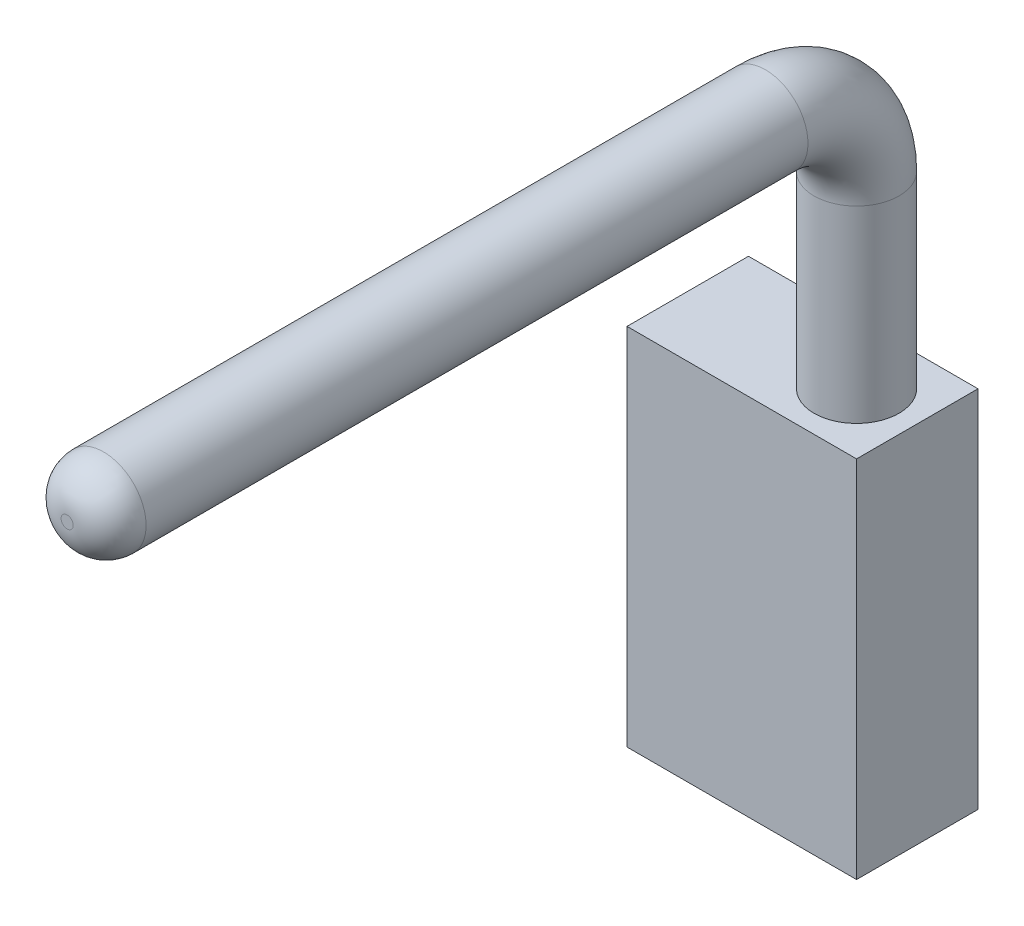
SolidWorks part; units mm, degrees
ref_plane "Front Plane" through (0, 0, 0) normal (1, 0, 0) x (0, 1, 0)
ref_plane "Top Plane" through (0, 0, 0) normal (0, 0, 1) x (0, 1, 0)
ref_plane "Right Plane" through (0, 0, 0) normal (0, 1, 0) x (-1, 0, 0)
sketch "Sketch1" plane through (0, 0, 0) normal (0, 0, 1) x (0, 1, 0)
  line L1 (-19.05, -12.0015) -> (19.05, -12.0015)
  line L2 (-19.05, -12.0015) -> (-19.05, 12.0015)
  line L3 (-19.05, 12.0015) -> (19.05, 12.0015)
  line L4 (19.05, -12.0015) -> (19.05, 12.0015)
  line L5 (-19.05, -12.0015) -> (19.05, 12.0015) construction
  line L6 (-19.05, 12.0015) -> (19.05, -12.0015) construction
  point P0 (0, 0)
  dimension "D1" = 38.1
  dimension "D2" = 24.003
extrude "Boss-Extrude1" add sketch "Sketch1" along normal blind 12.7
ref_plane "Plane1" through (5.6515, 0, 0) normal (1, 0, 0) x (0, 0, -1)
sketch "Sketch2" plane through (5.6515, 0, 0) normal (1, 0, 0) x (0, 0, -1)
  line L0 (-6.35, 19.05) -> (-6.35, 38.735)
  line L1 (-12.7, 19.05) -> (0, 19.05) construction
  line L2 (-15.875, 48.26) -> (-88.9, 48.26)
  arc A0 (-6.35, 38.735) -> (-15.875, 48.26) centre (-15.875, 38.735) ccw
  dimension "D1" = 9.525
  dimension "D2" = 82.55
  dimension "D3" = 29.21
sketch "Sketch3" plane through (0, 19.05, 0) normal (0, 1, 0) x (-1, 0, 0)
  line L0 (-5.6515, 15.875) -> (-5.6515, 6.35) construction
  line L1 (-5.6515, 6.985) -> (-5.6515, -6.985) construction
  circle A0 centre (-5.6515, 6.35) radius 4.445
  point P6 (-5.6515, 6.3902)
  dimension "D1" = 8.89
sweep "Sweep1" add profiles "Sketch3" path "Sketch2"
fillet "Fillet1" radius 3.81 1 edges at (5.6515, 43.815, 88.9)
